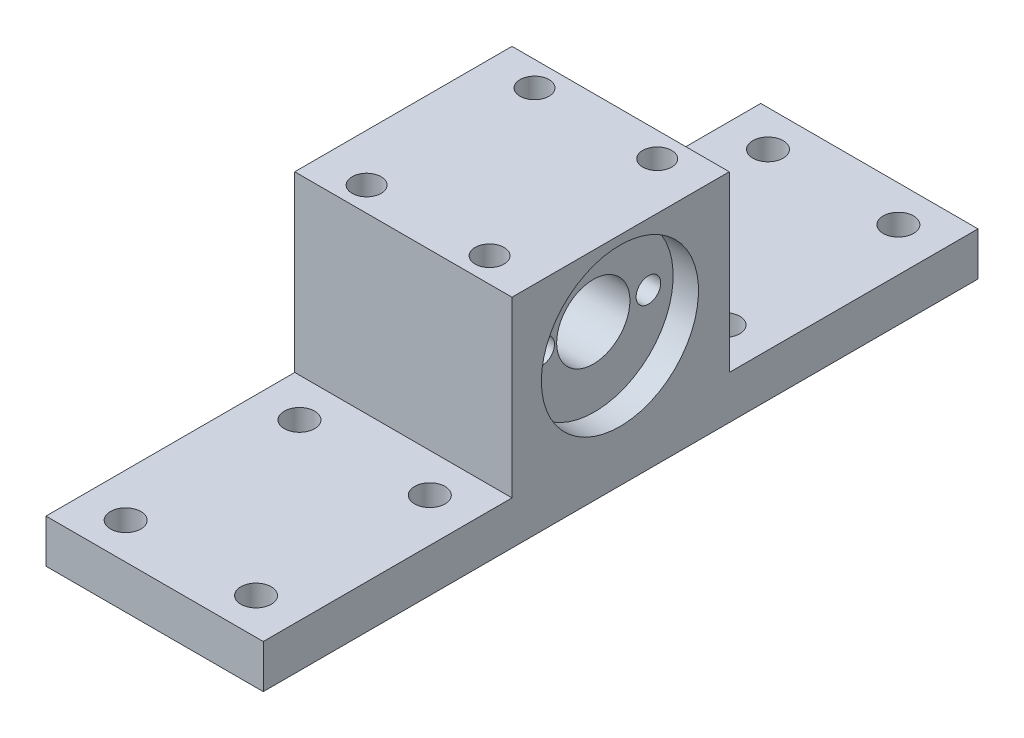
SolidWorks part; units mm, degrees
ref_plane "Спереди" through (0, 0, 0) normal (0, 0, 1) x (1, 0, 0)
ref_plane "Сверху" through (0, 0, 0) normal (0, 1, 0) x (1, 0, 0)
ref_plane "Справа" through (0, 0, 0) normal (1, 0, 0) x (0, 0, -1)
sketch "Эскиз1" plane through (0, 0, 0) normal (1, 0, 0) x (0, 0, -1)
  line L0 (-8.1967, 16.3378) -> (7.7033, 16.3378)
  line L1 (-8.1967, 16.3378) -> (-8.1967, 0.4378) construction
  line L2 (7.7033, 16.3378) -> (7.7033, 0.4378) construction
  line L3 (-8.1967, 0.4378) -> (7.7033, 0.4378) construction
  line L4 (-0.2467, 0.4378) -> (-0.2467, -4.5622) construction
  line L5 (-0.2467, -4.5622) -> (-0.2467, -12.4622) construction
  line L6 (-8.1967, 8.3878) -> (-13.1967, 8.3878) construction
  line L7 (15.0285, 20.4378) -> (15.0285, -3.5622)
  line L8 (-14.9715, 20.4378) -> (15.0285, 20.4378)
  line L9 (-49.3185, -3.5622) -> (-49.3185, -9.5622)
  line L10 (-49.3185, -9.5622) -> (49.3755, -9.5622)
  line L11 (49.3755, -3.5622) -> (49.3755, -9.5622)
  line L12 (4.8133, 8.3878) -> (6.8133, 8.3878) construction
  line L13 (-5.3067, 8.3878) -> (-7.3067, 8.3878) construction
  line L14 (0.0285, -23.4916) -> (0.0285, -33.1067) construction
  line L15 (49.3755, -3.5622) -> (15.0285, -3.5622)
  line L18 (-49.3185, -3.5622) -> (-14.9715, -3.5622)
  line L19 (-14.9715, 20.4378) -> (-14.9715, -3.5622)
  circle A0 centre (-0.2467, 16.3378) radius 7.95 construction
  circle A1 centre (-0.2467, 8.3878) radius 5.06
  circle A2 centre (7.3636, 8.3878) radius 1.7
  circle A3 centre (-32.3185, 7.9378) radius 4 construction
  circle A5 centre (-7.3067, 8.3878) radius 1.7
  circle A7 centre (32.3755, 7.9378) radius 4 construction
  point P0 (0, 0)
extrude "Бобышка-Вытянуть2" add sketch "Эскиз1" along normal blind 30
sketch "Эскиз3" plane through (0, -3.5622, 0) normal (0, 1, 0) x (1, 0, 0)
  line L0 (15, -0.0064) -> (15, 60.1741) construction
  line L1 (30, -32.145) -> (-7.2355, -32.145) construction
  line L2 (30, -49.3185) -> (30, -14.9715) construction
  line L3 (30, 0.0285) -> (-3.1763, 0.0285) construction
  line L5 (30, 32.202) -> (-7.2355, 32.202) construction
  circle A25 centre (6, -20.3185) radius 2.1
  circle A26 centre (24, -20.3185) radius 2.1
  circle A27 centre (24, -44.3185) radius 2.1
  circle A28 centre (6, -44.3185) radius 2.1
  circle A29 centre (6, 44.3755) radius 2.1
  circle A30 centre (24, 44.3755) radius 2.1
  circle A31 centre (24, 20.3755) radius 2.1
  circle A32 centre (6, 20.3755) radius 2.1
extrude "Вырез-Вытянуть1" cut sketch "Эскиз3" against normal through all both and the other way through all
sketch "Эскиз6" plane through (30, 0, 0) normal (1, 0, 0) x (0, 0, -1)
  circle A0 centre (-0.0679, 8.3651) radius 10.85
extrude "Вырез-Вытянуть2" cut sketch "Эскиз6" against normal blind 3.5 and the other way through all
sketch "Эскиз7" plane through (0, 0, 0) normal (-1, 0, 0) x (0, 0, 1)
  circle A0 centre (0.2467, 8.3878) radius 10.85
extrude "Вырез-Вытянуть3" cut sketch "Эскиз7" against normal blind 3.5
sketch "Эскиз8" plane through (0, 20.4378, 0) normal (0, 1, 0) x (1, 0, 0)
  line L0 (0, 0) -> (30, 0.0285) construction
  line L1 (30, -14.9715) -> (30, 15.0285) construction
  line L2 (15, 15.0285) -> (15, -14.9715) construction
  line L3 (30, 15.0285) -> (0, 15.0285) construction
  line L4 (30, -14.9715) -> (0, -14.9715) construction
  circle A0 centre (15, 0.0142) radius 7.1505 construction
  circle A1 centre (6.5291, 11.6094) radius 2
  circle A2 centre (23.4709, 11.6094) radius 2
  circle A3 centre (23.4929, -11.5649) radius 2
  circle A4 centre (6.5511, -11.597) radius 2
extrude "Вырез-Вытянуть4" cut sketch "Эскиз8" against normal blind 10
